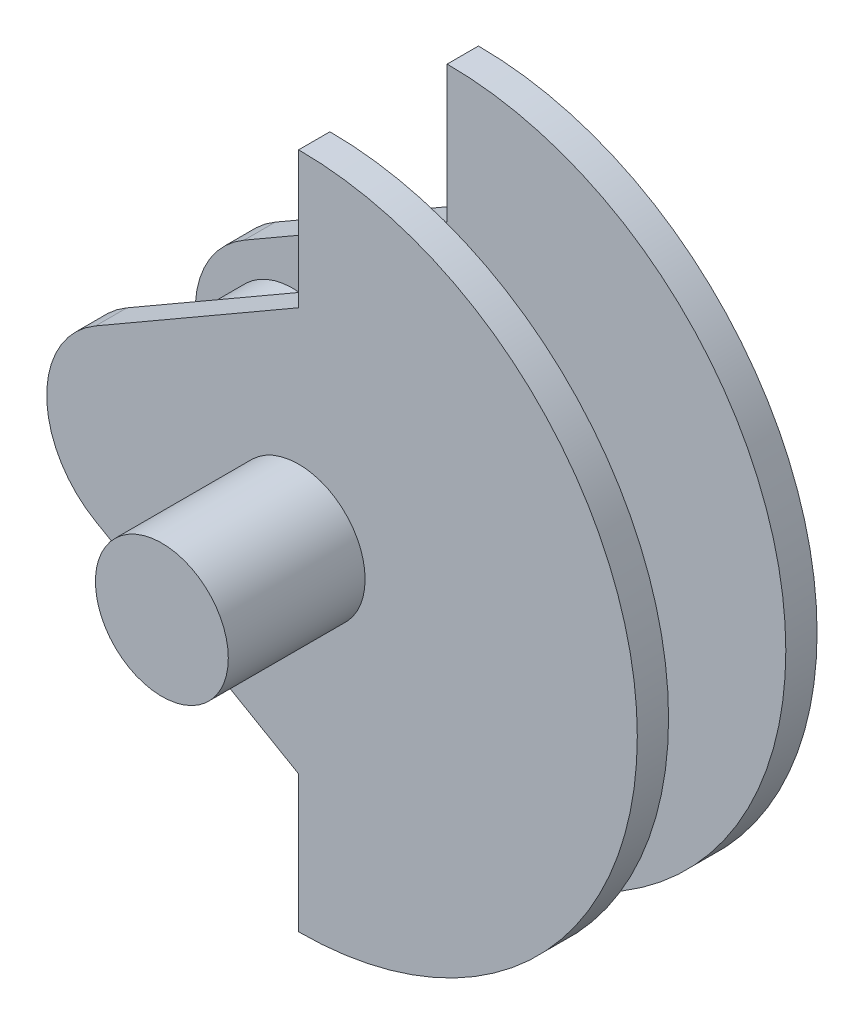
SolidWorks part; units mm, degrees
ref_plane "Front Plane" through (0, 0, 0) normal (0, 0, 1) x (1, 0, 0)
ref_plane "Top Plane" through (0, 0, 0) normal (0, 1, 0) x (1, 0, 0)
ref_plane "Right Plane" through (0, 0, 0) normal (1, 0, 0) x (0, 0, -1)
sketch "Sketch1" plane through (0, 0, 0) normal (0, 0, 1) x (1, 0, 0)
  line L0 (0, 0) -> (119.3333, 0) construction
  line L1 (-12.5, 21.6506) -> (39.4615, 51.6506)
  line L2 (-12.5, -21.6506) -> (39.4615, -51.6506)
  line L3 (39.4615, 86.6506) -> (39.4615, 51.6506)
  line L4 (39.4615, -51.6506) -> (39.4615, -86.6506)
  arc A1 (-12.5, 21.6506) -> (-12.5, -21.6506) centre (0, 0) ccw
  arc A3 (39.4615, -86.6506) -> (39.4615, 86.6506) centre (39.4615, 0) ccw
  dimension "D1" = 30
  dimension "D2" = 60
  dimension "D3" = 35
  dimension "D5" = 60
extrude "Boss-Extrude1" add sketch "Sketch1" along normal blind 8
sketch "Sketch5" plane through (0, 0, 0) normal (0, 0, -1) x (-1, 0, 0)
  line L3 (-39.4615, 86.6506) -> (-39.4615, 51.6506)
  line L4 (-39.4615, 86.6506) -> (-39.4615, 51.6506)
  line L8 (-39.4615, 51.6506) -> (12.5, 21.6506)
  line L9 (-39.4615, 51.6506) -> (12.5, 21.6506)
  line L11 (12.5, -21.6506) -> (-39.4615, -51.6506)
  line L12 (12.5, -21.6506) -> (-39.4615, -51.6506)
  line L14 (-39.4615, -51.6506) -> (-39.4615, -86.6506)
  line L15 (-39.4615, -51.6506) -> (-39.4615, -86.6506)
  arc A5 (-39.4615, 86.6506) -> (-39.4615, -86.6506) centre (-39.4615, 0) ccw
  arc A6 (-39.4615, 86.6506) -> (-39.4615, -86.6506) centre (-39.4615, 0) ccw
  arc A8 (12.5, -21.6506) -> (12.5, 21.6506) centre (0, 0) ccw
  arc A9 (12.5, -21.6506) -> (12.5, 21.6506) centre (0, 0) ccw
  dimension "D1" = 0
  dimension "D2" = 0
  dimension "D3" = 0
  dimension "D4" = 0
  dimension "D5" = 0
  dimension "D6" = 0
extrude "Boss-Extrude4" add sketch "Sketch5" along normal blind 8 from offset 30 separate body
sketch "Sketch7" plane through (0, 0, 8) normal (0, 0, 1) x (1, 0, 0)
  circle A10 centre (0, 0) radius 17.223
  arc A11 (-12.5, 21.6506) -> (-12.5, -21.6506) centre (0, 0) ccw
  arc A12 (-12.5, 21.6506) -> (-12.5, -21.6506) centre (0, 0) ccw
  dimension "D3" = 34.4461
  dimension "D1" = 0
extrude "Boss-Extrude5" add sketch "Sketch7" against normal blind 38 contours A10
sketch "Sketch8" plane through (0, 0, 8) normal (0, 0, 1) x (1, 0, 0)
  circle A2 centre (39.4615, 0) radius 17
  dimension "D2" = 34
extrude "Boss-Extrude6" add sketch "Sketch8" along normal blind 35
sketch "Sketch9" plane through (0, 0, -38) normal (0, 0, -1) x (-1, 0, 0)
  circle A8 centre (-39.4615, 0) radius 17
  circle A9 centre (-39.4615, 0) radius 17
  dimension "D2" = 0
extrude "Boss-Extrude7" add sketch "Sketch9" along normal blind 35
